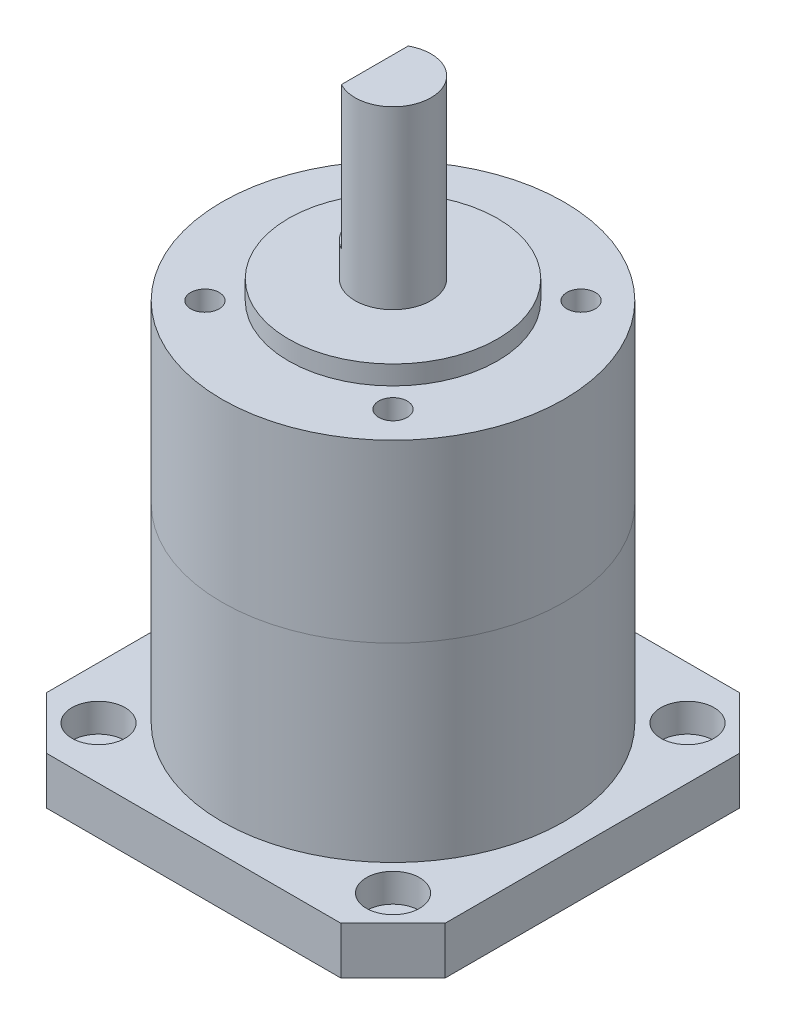
SolidWorks part; units mm, degrees
ref_plane "前视基准面" through (0, 0, 0) normal (0, 0, 1) x (1, 0, 0)
ref_plane "上视基准面" through (0, 0, 0) normal (0, 1, 0) x (1, 0, 0)
ref_plane "右视基准面" through (0, 0, 0) normal (1, 0, 0) x (0, 0, -1)
sketch "草图1" plane through (0, 0, 0) normal (0, 1, 0) x (1, 0, 0)
  line L1 (-21, 21) -> (21, 21)
  line L2 (-21, 21) -> (-21, -21)
  line L3 (-21, -21) -> (21, -21)
  line L4 (21, 21) -> (21, -21)
  line L5 (-21, 21) -> (21, -21) construction
  line L6 (-21, -21) -> (21, 21) construction
  point P0 (0, 0)
  dimension "D1" = 42
extrude "凸台-拉伸1" add sketch "草图1" along normal blind 5
chamfer "倒角1" distance 5.5 4 edges at (-21, 2.5, 21) (21, 2.5, 21) (21, 2.5, -21) (-21, 2.5, -21)
sketch "草图2" plane through (0, 0, 0) normal (0, -1, 0) x (1, 0, 0)
  line L0 (10.1924, 0) -> (-10.1924, 0) construction
  line L1 (0, 0) -> (0, 29.6141) construction
  line L2 (-3.6102, 3.6102) -> (-29.2181, 29.2181) construction
  line L3 (9.2594, 9.2594) -> (34.522, 34.522) construction
  circle A0 centre (-15.5, 15.5) radius 1.5
  circle A1 centre (15.5, 15.5) radius 1.5
  circle A2 centre (15.5, -15.5) radius 1.5
  circle A3 centre (-15.5, -15.5) radius 1.5
  point P2 (0, 0)
  point P13 (0, 0)
  point P22 (0, 0)
  dimension "D2" = 3
  dimension "D1" = 45
  dimension "D3" = 15.5
  dimension "D4" = 4
extrude "切除-拉伸1" cut sketch "草图2" against normal up to surface (5 mm away) up to face at (0, 5, 0)
sketch "草图3" plane through (0, 5, 0) normal (0, 1, 0) x (1, 0, 0)
  circle A0 centre (0, 0) radius 18
  dimension "D1" = 36
extrude "凸台-拉伸2" add sketch "草图3" along normal blind 38.5
sketch "草图4" plane through (0, 43.5, 0) normal (0, 1, 0) x (1, 0, 0)
  line L0 (0, 0) -> (31.2836, 0) construction
  line L1 (0, 0) -> (0, 33.2252) construction
  line L2 (0, 0) -> (-16.9551, 16.9551) construction
  circle A0 centre (-9.8995, 9.8995) radius 1.5
  circle A1 centre (0, 0) radius 14
  circle A2 centre (9.8995, 9.8995) radius 1.5
  circle A3 centre (9.8995, -9.8995) radius 1.5
  circle A4 centre (-9.8995, -9.8995) radius 1.5
  point P20 (0, 0)
  dimension "D2" = 3
  dimension "D3" = 28
  dimension "D1" = 45
  dimension "D4" = 4
extrude "切除-拉伸2" cut sketch "草图4" against normal blind 4 contours A0 | A2 | A3 | A4
sketch "草图6" plane through (0, 43.5, 0) normal (0, 1, 0) x (1, 0, 0)
  circle A0 centre (0, 0) radius 11
  dimension "D1" = 22
extrude "凸台-拉伸3" add sketch "草图6" along normal blind 2 contours A0
sketch "草图7" plane through (0, 45.5, 0) normal (0, 1, 0) x (1, 0, 0)
  circle A0 centre (0, 0) radius 4
  dimension "D1" = 8
extrude "凸台-拉伸4" add sketch "草图7" along normal blind 18.5
sketch "草图8" plane through (0, 0, 0) normal (0, -1, 0) x (1, 0, 0)
  circle A0 centre (0, 0) radius 11
  dimension "D1" = 22
extrude "切除-拉伸3" cut sketch "草图8" against normal blind 3
sketch "草图9" plane through (0, 3, 0) normal (0, -1, 0) x (1, 0, 0)
  circle A0 centre (0, 0) radius 8
  dimension "D1" = 16
extrude "切除-拉伸4" cut sketch "草图9" against normal blind 10
ref_plane "基准面1" through (0, 25, 0) normal (0, 1, 0) x (1, 0, 0)
split line "分割线1"
sketch "草图11" plane through (0, 64, 0) normal (0, 1, 0) x (1, 0, 0)
  line L0 (-1.9142, 3.5122) -> (-1.9142, -3.5122)
  circle A0 centre (0, 0) radius 4
  circle A2 centre (0, 0) radius 4
  circle A3 centre (0, 0) radius 4
  circle M3 centre (0, 0) radius 4
  dimension "D1" = 0
extrude "切除-拉伸5" cut sketch "草图11" against normal blind 15 contours L0 M3
sketch "草图12" plane through (0, 5, 0) normal (0, 1, 0) x (1, 0, 0)
  circle A0 centre (-15.5, 15.5) radius 2.8
  circle A1 centre (15.5, 15.5) radius 2.8
  circle A2 centre (-15.5, -15.5) radius 2.8
  circle A3 centre (15.5, -15.5) radius 2.8
  dimension "D1" = 5.6
extrude "切除-拉伸6" cut sketch "草图12" against normal blind 3
